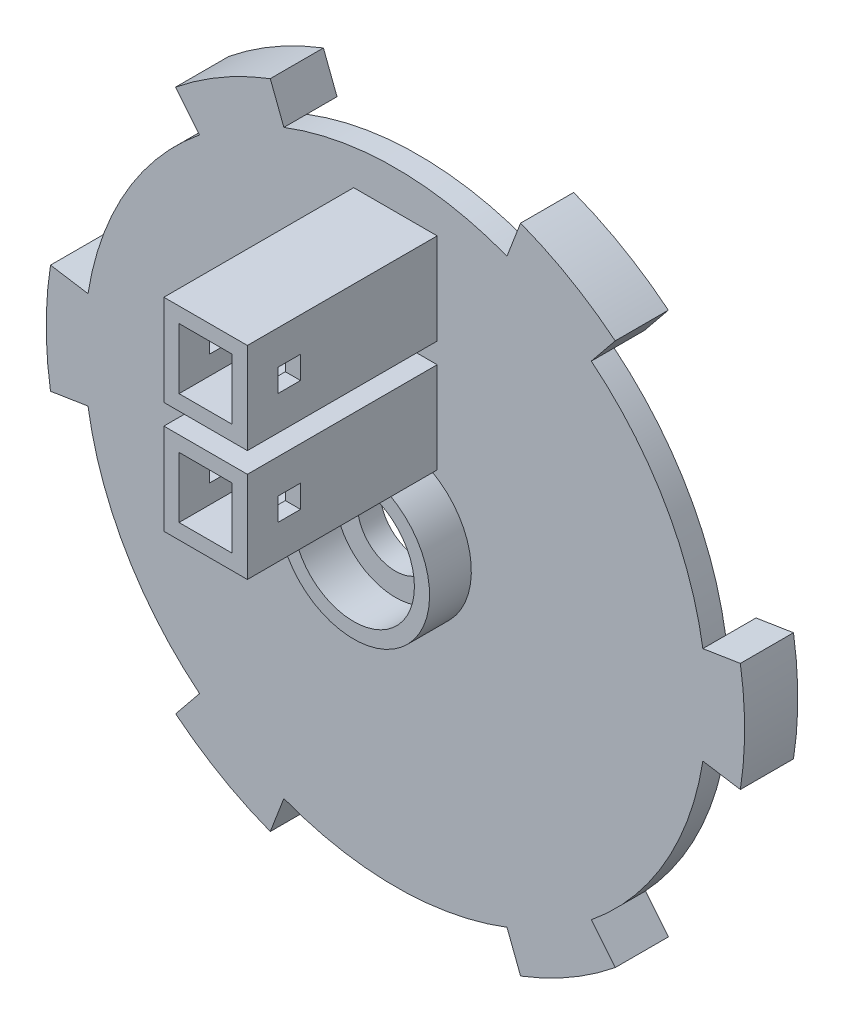
SolidWorks part; units mm, degrees
ref_plane "Front Plane" through (0, 0, 0) normal (0, 0, 1) x (1, 0, 0)
ref_plane "Top Plane" through (0, 0, 0) normal (0, 1, 0) x (1, 0, 0)
ref_plane "Right Plane" through (0, 0, 0) normal (1, 0, 0) x (0, 0, -1)
sketch "Sketch1" plane through (0, 0, 0) normal (0, 0, 1) x (1, 0, 0)
  circle A0 centre (0, 0) radius 41
  circle A1 centre (0, 0) radius 5
  dimension "D1" = 82
  dimension "D2" = 10
extrude "Boss-Extrude1" add sketch "Sketch1" along normal blind 3
sketch "Sketch2" plane through (0, 0, 3) normal (0, 0, 1) x (1, 0, 0)
  line L1 (-5.5, 36) -> (5.5, 36)
  line L2 (-5.5, 36) -> (-5.5, 24)
  line L3 (-5.5, 24) -> (5.5, 24)
  line L4 (5.5, 36) -> (5.5, 24)
  line L5 (-5.5, 21.3014) -> (5.5, 21.3014)
  line L6 (-5.5, 21.3014) -> (-5.5, 9.3014)
  line L7 (-5.5, 9.3014) -> (5.5, 9.3014)
  line L8 (5.5, 21.3014) -> (5.5, 9.3014)
  point P14 (0, 9.3014)
  point P16 (0, 24)
  point P17 (5.5, 30)
  dimension "D1" = 30
  dimension "D2" = 22
  dimension "D4" = 12
  dimension "D6" = 11
extrude "Boss-Extrude2" add sketch "Sketch2" along normal blind 25
sketch "Sketch3" plane through (0, 0, 28) normal (0, 0, 1) x (1, 0, 0)
  line L0 (-5.5, 9.3014) -> (5.5, 9.3014) construction
  line L1 (-3.5, 34) -> (3.5, 34)
  line L2 (-3.5, 34) -> (-3.5, 26)
  line L3 (-3.5, 26) -> (3.5, 26)
  line L4 (3.5, 34) -> (3.5, 26)
  line L5 (-3.5, 19.3014) -> (3.5, 19.3014)
  line L6 (-3.5, 19.3014) -> (-3.5, 11.3014)
  line L7 (-3.5, 11.3014) -> (3.5, 11.3014)
  line L8 (3.5, 19.3014) -> (3.5, 11.3014)
  line L10 (5.5, 24) -> (5.5, 36) construction
  line L11 (-5.5, 24) -> (5.5, 24) construction
  line L12 (5.5, 9.3014) -> (5.5, 21.3014) construction
  point P10 (0, 11.3014)
  point P17 (3.5, 30)
  point P20 (0, 26)
  dimension "D1" = 8
  dimension "D2" = 7
  dimension "D3" = 2
  dimension "D4" = 2
  dimension "D5" = 2
  dimension "D6" = 2
extrude "Cut-Extrude1" cut sketch "Sketch3" against normal through all
sketch "Sketch4" plane through (5.5, 0, 0) normal (1, 0, 0) x (0, 0, -1)
  line L0 (-28, 24) -> (-28, 36) construction
  line L1 (-24, 16.8014) -> (-21, 16.8014)
  line L2 (-24, 16.8014) -> (-24, 13.8014)
  line L3 (-24, 13.8014) -> (-21, 13.8014)
  line L4 (-21, 16.8014) -> (-21, 13.8014)
  line L5 (-24, 31.5) -> (-21, 31.5)
  line L6 (-24, 31.5) -> (-24, 28.5)
  line L7 (-24, 28.5) -> (-21, 28.5)
  line L8 (-21, 31.5) -> (-21, 28.5)
  line L9 (-28, 9.3014) -> (-28, 21.3014) construction
  point P11 (-28, 15.3014)
  point P15 (-24, 15.3014)
  point P16 (-24, 30)
  point P17 (-28, 30)
  dimension "D1" = 3
  dimension "D2" = 4
  dimension "D3" = 4
extrude "Cut-Extrude2" cut sketch "Sketch4" against normal through all
sketch "Sketch5" plane through (0, 0, 3) normal (0, 0, 1) x (1, 0, 0)
  line L14 (-5.5, 36) -> (-5.5, 24) construction
  line L15 (-5.5, 24) -> (5.5, 24) construction
  line L26 (16.4849, 42.9447) -> (14.6931, 38.2768)
  line L27 (25.8021, 31.863) -> (28.9487, 35.7487)
  line L28 (45.4336, 7.196) -> (40.4952, 6.4138)
  line L29 (40.4952, -6.4138) -> (45.4336, -7.196)
  line L30 (28.9487, -35.7487) -> (25.8021, -31.863)
  line L31 (14.6931, -38.2768) -> (16.4849, -42.9447)
  line L32 (-16.4849, -42.9447) -> (-14.6931, -38.2768)
  line L33 (-25.8021, -31.863) -> (-28.9487, -35.7487)
  line L34 (-45.4336, -7.196) -> (-40.4952, -6.4138)
  line L35 (-40.4952, 6.4138) -> (-45.4336, 7.196)
  line L36 (-28.9487, 35.7487) -> (-25.8021, 31.863)
  line L37 (-14.6931, 38.2768) -> (-16.4849, 42.9447)
  arc A1 (14.6931, 38.2768) -> (25.8021, 31.863) centre (0, 0) cw
  arc A6 (16.4849, 42.9447) -> (28.9487, 35.7487) centre (0, 0) cw
  arc A18 (45.4336, 7.196) -> (45.4336, -7.196) centre (0, 0) cw
  arc A19 (40.4952, 6.4138) -> (40.4952, -6.4138) centre (0, 0) cw
  arc A20 (28.9487, -35.7487) -> (16.4849, -42.9447) centre (0, 0) cw
  arc A21 (25.8021, -31.863) -> (14.6931, -38.2768) centre (0, 0) cw
  arc A22 (-16.4849, -42.9447) -> (-28.9487, -35.7487) centre (0, 0) cw
  arc A23 (-14.6931, -38.2768) -> (-25.8021, -31.863) centre (0, 0) cw
  arc A24 (-45.4336, -7.196) -> (-45.4336, 7.196) centre (0, 0) cw
  arc A25 (-40.4952, -6.4138) -> (-40.4952, 6.4138) centre (0, 0) cw
  arc A26 (-28.9487, 35.7487) -> (-16.4849, 42.9447) centre (0, 0) cw
  arc A27 (-25.8021, 31.863) -> (-14.6931, 38.2768) centre (0, 0) cw
  point P31 (0, 0)
  dimension "D1" = 14.392
  dimension "D3" = 46
  dimension "D2" = 41
  dimension "D6" = 5.5
  dimension "D7" = 7.863
  dimension "D4" = 46
  dimension "D5" = 46
extrude "Boss-Extrude3" add sketch "Sketch5" against normal blind 7
sketch "Sketch6" plane through (0, 0, 3) normal (0, 0, 1) x (1, 0, 0)
  circle A0 centre (0, 0) radius 8
  circle A1 centre (0, 0) radius 10
  dimension "D1" = 16
  dimension "D2" = 20
extrude "Boss-Extrude4" add sketch "Sketch6" along normal blind 5.5
